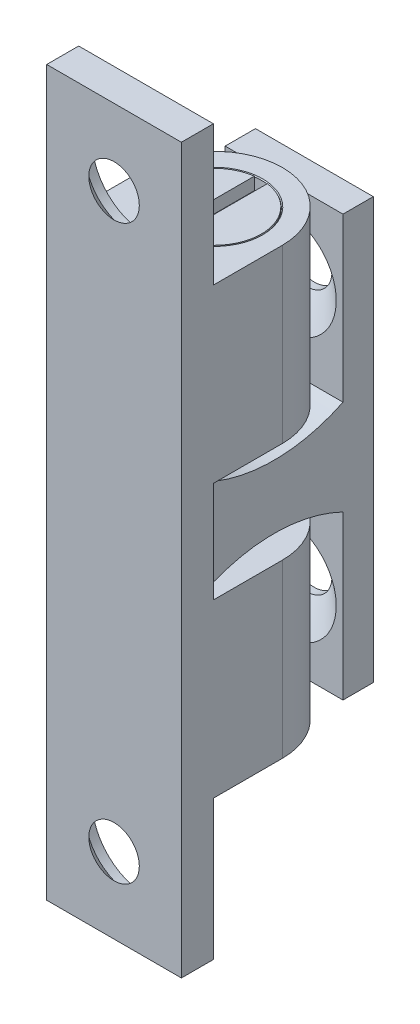
SolidWorks part; units mm, degrees
ref_plane "Front Plane" through (0, 0, 0) normal (0, 0, 1) x (1, 0, 0)
ref_plane "Top Plane" through (0, 0, 0) normal (0, 1, 0) x (1, 0, 0)
ref_plane "Right Plane" through (0, 0, 0) normal (1, 0, 0) x (0, 0, -1)
sketch "Sketch1" plane through (0, 0, 0) normal (1, 0, 0) x (0, 0, -1)
  line L0 (5.95, 0) -> (-5.95, 0) construction
  line L1 (-5.95, -21.4998) -> (-5.95, 21.4998) construction
  line L2 (0, 0) -> (0, 21.4998) construction
  line L3 (5.95, -12.5006) -> (5.95, 12.5006) construction
  line L4 (5.95, -7.8499) -> (5.95, 7.8499) construction
  line L5 (-5.95, -17) -> (-5.95, 17) construction
  line L6 (-5.95, 21.4998) -> (-4.05, 21.4998) construction
  line L7 (-4.05, 21.4998) -> (-4.05, 0) construction
  line L8 (5.95, 12.5006) -> (4.15, 12.5006) construction
  line L9 (-4.05, 13.2) -> (4.0501, 13.2) construction
  line L10 (-4.05, 13.2) -> (-4.05, 3) construction
  line L11 (-4.05, 3) -> (4.0501, 3) construction
  line L12 (4.0501, 13.2) -> (4.0501, 3) construction
  line L13 (4.15, 12.5006) -> (4.15, 0) construction
  line L14 (-4.05, 0) -> (-4.05, 2.825) construction
  line L15 (-4.05, 2.825) -> (4.15, 2.825) construction
  line L16 (4.15, 4.7499) -> (4.15, 10.9499) construction
  line L17 (5.95, 6.35) -> (5.95, 9.3497) construction
  line L18 (5.95, 9.3497) -> (4.15, 9.3497) construction
  line L19 (5.95, 8.8047) -> (4.15, 10.9499) construction
  line L20 (-5.95, 15.5001) -> (-5.95, 18.4999) construction
  line L23 (-4.05, 20.2) -> (-4.05, 13.8) construction
  line L25 (-5.95, 18.4999) -> (-4.9262, 19.72) construction
  line L26 (-4.9262, 19.72) -> (-4.9262, 20.2) construction
  line L27 (-4.9262, 20.2) -> (-4.05, 20.2) construction
  line L28 (-5.95, 15.5001) -> (-4.9262, 14.28) construction
  line L29 (-4.9262, 14.28) -> (-4.9262, 13.8) construction
  line L30 (-4.9262, 13.8) -> (-4.05, 13.8) construction
  line L31 (-5.95, 17) -> (-4.05, 17) construction
  arc A0 (-4.05, 2.825) -> (4.15, 2.825) centre (0.05, 11.2798) ccw construction
  point P0 (4.0501, 0)
  point P4 (0, 0)
  point P8 (-5.95, 0)
  point P11 (-4.05, 0)
  point P14 (5.95, 0)
  point P18 (5.95, 0)
  point P21 (-5.95, 0)
  point P31 (4.0501, 3.5)
  point P33 (0.05, 1.8833)
  point P39 (4.15, 7.8499)
  point P42 (5.95, 7.8499)
  point P45 (-5.95, 17)
  point P46 (-4.05, 17)
  dimension "Height" = 42.9997
  dimension "Strike Plate Height" = 25.0012
  dimension "Strike Plate Depth" = 10
  dimension "Strike Plate Mounting Hole Center to Center Distance" = 15.6997
  dimension "Mounting Hole Center to Center Distance" = 34
  dimension "Latch Gap" = 6
  dimension "Thickness" = 1.9
  dimension "Ball Housing Width" = 10.2
  dimension "Strike Plate Thickness" = 1.8
  dimension "Latch Width" = 5.65
  dimension "D1" = 3.7667
  dimension "D2" = 0.5
  dimension "Strike Plate Mounting Hole CSK" = 6.2
  dimension "Strike Plate Mounting Hole Diameter" = 2.9997
  dimension "Mounting Hole CSK" = 6.4
  dimension "Mounting Hole Diameter" = 2.9997
  dimension "D3" = 100
  dimension "D6" = 50
  dimension "D7" = 5.44
  dimension "D5" = 50
  dimension "Depth" = 8.1001
sketch "Sketch2" plane through (0, 0, 0) normal (0, 1, 0) x (1, 0, 0)
  line L0 (4.0005, -5.95) -> (-4.0005, -5.95) construction
  line L1 (-2.025, 0) -> (2.025, 0) construction
  line L2 (3.5001, 5.95) -> (-3.5001, 5.95) construction
  line L3 (0, -4.05) -> (0, 4.0501) construction
  line L4 (0, -4.05) -> (0, 4.0501) construction
  line L6 (0, 0) -> (0, 4.0501) construction
  circle A0 centre (0, 0) radius 2.025 construction
  point P4 (0, -5.95)
  point P9 (0, 5.95)
  dimension "Width" = 8.001
  dimension "Strike Plate Width" = 7.0002
sketch "Sketch3" plane through (0, 0, 0) normal (1, 0, 0) x (0, 0, -1)
  line L0 (-4.05, 13.2) -> (-4.05, 21.4998)
  line L1 (-5.95, 0) -> (-4.05, 0) construction
  line L2 (-5.95, -21.4998) -> (-5.95, 21.4998)
  line L3 (-5.95, 21.4998) -> (-4.05, 21.4998)
  line L4 (-4.05, -3) -> (-4.05, 3)
  line L5 (-4.05, 13.2) -> (4.0501, 13.2)
  line L7 (-4.05, 3) -> (4.0501, 3)
  line L8 (4.0501, 13.2) -> (4.0501, 3)
  line L9 (4.0501, -13.2) -> (4.0501, -3)
  line L10 (-4.05, -3) -> (4.0501, -3)
  line L11 (-4.05, -13.2) -> (4.0501, -13.2)
  line L12 (-5.95, -21.4998) -> (-4.05, -21.4998)
  line L13 (-4.05, -13.2) -> (-4.05, -21.4998)
extrude "Boss-Extrude1" add sketch "Sketch3" against normal up to vertex (4.0005 mm away) and the other way up to vertex (4.0005 mm away) up to point (-4.0005, 0, 5.95) other way up to point (4.0005, 0, 5.95)
sketch "Sketch4" plane through (0, 0, 0) normal (1, 0, 0) x (0, 0, -1)
  line L0 (4.15, 2.825) -> (4.15, 12.5006)
  line L1 (4.15, 12.5006) -> (5.95, 12.5006)
  line L2 (5.95, 12.5006) -> (5.95, -12.5006)
  line L3 (5.95, 0) -> (-4.05, 0) construction
  line L4 (-4.05, -2.825) -> (-4.05, 2.825)
  line L5 (4.15, -12.5006) -> (5.95, -12.5006)
  line L6 (4.15, -2.825) -> (4.15, -12.5006)
  arc A0 (-4.05, 2.825) -> (4.15, 2.825) centre (0.05, 11.2798) ccw construction
  arc A1 (-4.05, 2.825) -> (4.15, 2.825) centre (0.05, 11.2798) ccw
  arc A2 (-4.05, -2.825) -> (4.15, -2.825) centre (0.05, -11.2798) cw
extrude "Boss-Extrude2" add sketch "Sketch4" along normal up to vertex (3.5001 mm away) and the other way up to vertex (3.5001 mm away) separate body up to point (3.5001, 0, -5.95) other way up to point (-3.5001, 0, -5.95)
sketch "Sketch5" plane through (0, 13.2, 0) normal (0, 1, 0) x (1, 0, 0)
  line L1 (0, -4.05) -> (0, 4.0501) construction
  line L2 (-4.0005, -5.95) -> (-4.0005, 0.0496) construction
  line L3 (-4.0005, 0.0496) -> (-4.0005, 4.0501)
  line L4 (-4.0005, 4.0501) -> (0, 4.0501)
  line L5 (0, 4.0501) -> (4.0005, 4.0501)
  line L6 (4.0005, 4.0501) -> (4.0005, 0.0496)
  arc A1 (4.0005, 0.0496) -> (-4.0005, 0.0496) centre (0, 0.0496) ccw
  line M4 (4.0005, -4.05) -> (4.0005, 4.0501)
  line M5 (4.0005, 4.0501) -> (-4.0005, 4.0501)
  line M6 (-4.0005, 4.0501) -> (-4.0005, -4.05)
extrude "Cut-Extrude1" cut sketch "Sketch5" against normal through all contours A1 M5 M6 | A1 M4 M5
ref_plane "Plane1" through (0, 3.5, 0) normal (0, 1, 0) x (1, 0, 0)
sketch "Sketch6" plane through (0, 3.5, 0) normal (0, 1, 0) x (1, 0, 0)
  line L0 (-2.025, 0) -> (2.025, 0) construction
  line L1 (-2.025, 0) -> (2.025, 0)
  circle A0 centre (0, 0) radius 2.025 construction
  arc A1 (2.025, 0) -> (-2.025, 0) centre (0, 0) ccw
revolve "Cut-Revolve1" cut sketch "Sketch6" angle 360 about L1
sketch "Sketch7" plane through (0, 3.5, 0) normal (0, 1, 0) x (1, 0, 0)
  line L0 (-2.025, 0) -> (2.025, 0) construction
  line L1 (-2.025, 0) -> (2.025, 0)
  circle A0 centre (0, 0) radius 2.025 construction
  arc A1 (2.025, 0) -> (-2.025, 0) centre (0, 0) ccw
revolve "Revolve1" add sketch "Sketch7" angle 360 about L1
sketch "Sketch13" plane through (0, 13.2, 0) normal (0, 1, 0) x (1, 0, 0)
  circle A0 centre (0, 0) radius 2.8258
  circle A1 centre (0, 0) radius 2.8004 construction
  dimension "D1" = 5.6007
extrude "Cut-Extrude2" cut sketch "Sketch13" against normal blind 1.275
sketch "Sketch15" plane through (0, 11.925, 0) normal (0, 1, 0) x (1, 0, 0)
  circle A0 centre (0, 0) radius 2.8004 construction
  circle A1 centre (0, 0) radius 2.8004
extrude "Boss-Extrude3" add sketch "Sketch15" along normal up to surface (1.275 mm away) separate body up to face at (0, 13.2, 2.8258)
sketch "Sketch14" plane through (0, 13.2, 0) normal (0, 1, 0) x (1, 0, 0)
  line L0 (-0.3864, 2.7736) -> (-0.3864, -2.7736)
  line L2 (0.3864, 2.7736) -> (0.3864, -2.7736)
  line L4 (-0.3864, 0) -> (0.3864, 0) construction
  circle A0 centre (0, 0) radius 2.8004 construction
  arc A1 (-0.3864, -2.7736) -> (0.3864, -2.7736) centre (0, 0) ccw
  arc A2 (0.3864, 2.7736) -> (-0.3864, 2.7736) centre (0, 0) ccw
  dimension "D1" = 0.7729
extrude "Cut-Extrude4" cut sketch "Sketch14" against normal blind 0.7497
sketch "Sketch9" plane through (0, 0, 0) normal (1, 0, 0) x (0, 0, -1)
  line L4 (-5.95, 18.4999) -> (-5.95, 17)
  line L5 (-5.95, 17) -> (-4.05, 17)
  line L6 (-4.05, 21.4998) -> (-4.05, 0) construction
  line L7 (-4.05, 17) -> (-4.05, 20.2)
  line L8 (-5.95, 18.4999) -> (-4.9262, 19.72)
  line L9 (-4.9262, 19.72) -> (-4.9262, 20.2)
  line L10 (-4.9262, 20.2) -> (-4.05, 20.2)
revolve "Cut-Revolve2" cut sketch "Sketch9" angle 360 about L5
mirror "Mirror1" about plane through (0, 0, 0) normal (0, 1, 0) of "Cut-Revolve2", "Cut-Revolve1", "Cut-Extrude2"
mirror "Mirror3" about plane through (0, 0, 0) normal (0, 1, 0) of bodies 109 127
fillet "Fillet1" radius 0.5 2 edges at (0, -2.825, 4.05) (0, 2.825, 4.05)
sketch "Sketch12" plane through (0, 0, 0) normal (1, 0, 0) x (0, 0, -1)
  line L0 (4.15, 9.3497) -> (5.95, 9.3497)
  line L1 (5.95, 9.3497) -> (5.95, 7.8499)
  line L2 (5.95, 7.8499) -> (4.15, 7.8499)
  line L3 (4.15, 7.8499) -> (4.15, 9.3497)
revolve "Cut-Revolve4" cut sketch "Sketch12" angle 360 about L2
sketch "Sketch10" plane through (0, 0, 0) normal (1, 0, 0) x (0, 0, -1)
  line L0 (4.15, 7.8499) -> (4.15, 10.9499)
  line L1 (4.15, 10.9499) -> (5.95, 8.8047)
  line L3 (5.95, 8.8047) -> (5.95, 7.8499)
  line L4 (5.95, 7.8499) -> (4.15, 7.8499)
revolve "Cut-Revolve3" cut sketch "Sketch10" angle 360 about L4
mirror "Mirror4" about plane through (0, 0, 0) normal (0, 1, 0) of "Cut-Revolve3", "Cut-Revolve4"
chamfer "Chamfer1" distance 0.056 angle 45 2 edges at (0, 13.2, 2.8258) (0, -13.2, 2.8258)
move or copy body "Body-Move/Copy1" bodies to move or copy 125 copy yes number of copies 1 translate (0, 0, -20) parameters "D1"=0, "D2"=0, "D3"=20
sketch "Sketch11" plane through (0, 0, 0) normal (1, 0, 0) x (0, 0, -1)
  line L6 (15.95, 2.0613) -> (15.95, -2.0613)
  line L7 (24.15, -2.825) -> (24.15, -12.5006)
  line L8 (24.15, -12.5006) -> (25.95, -12.5006)
  line L9 (25.95, -12.5006) -> (25.95, 12.5006)
  line L10 (25.95, 12.5006) -> (24.15, 12.5006)
  line L11 (24.15, 12.5006) -> (24.15, 2.825)
  line L12 (15.95, 2.0613) -> (15.95, -2.0613)
  line L13 (24.15, -2.825) -> (24.15, -12.5006)
  line L14 (24.15, -12.5006) -> (25.95, -12.5006)
  line L15 (25.95, -12.5006) -> (25.95, 12.5006)
  line L16 (25.95, 12.5006) -> (24.15, 12.5006)
  line L17 (24.15, 12.5006) -> (24.15, 2.825)
  arc A8 (15.95, -2.0613) -> (16.6319, -2.5271) centre (16.45, -2.0613) ccw
  arc A9 (24.15, -2.825) -> (16.6319, -2.5271) centre (20.05, -11.2798) ccw
  arc A10 (16.6319, 2.5271) -> (24.15, 2.825) centre (20.05, 11.2798) ccw
  arc A11 (15.95, -2.0613) -> (16.6319, -2.5271) centre (16.45, -2.0613) ccw
  arc A13 (24.15, -2.825) -> (16.6319, -2.5271) centre (20.05, -11.2798) ccw
  arc A14 (16.6319, 2.5271) -> (24.15, 2.825) centre (20.05, 11.2798) ccw
  arc A16 (16.6319, 2.5271) -> (15.95, 2.0613) centre (16.45, 2.0613) ccw
  arc A17 (16.6319, 2.5271) -> (15.95, 2.0613) centre (16.45, 2.0613) ccw
  dimension "D1" = 0
delete or keep bodies "Body-Delete/Keep 1" type delete bodies bodies 118
equation "\"D1@Sketch1\"=\"Latch Width@Sketch1\" * 2 / 3"
equation "\"D1@Fillet1\"=\"Strike Plate Height@Sketch1\"/50"
equation "\"D6@Sketch1\"=\"D3@Sketch1\"/2"
equation "\"D7@Sketch1\"=\"Mounting Hole CSK@Sketch1\"*.85"
equation "\"D1@Cut-Extrude2\"=\"Ball Housing Width@Sketch1\"*.125"
equation "\"D1@Chamfer1\"=\"D1@Sketch13\"*.01"
equation "\"D1@Sketch13\"=\"Width@Sketch2\"*.7"
equation "\"D1@Sketch14\"=\"D1@Sketch13\"*.138"
equation "\"D1@Cut-Extrude4\"=\"D1@Sketch14\"*.97"
